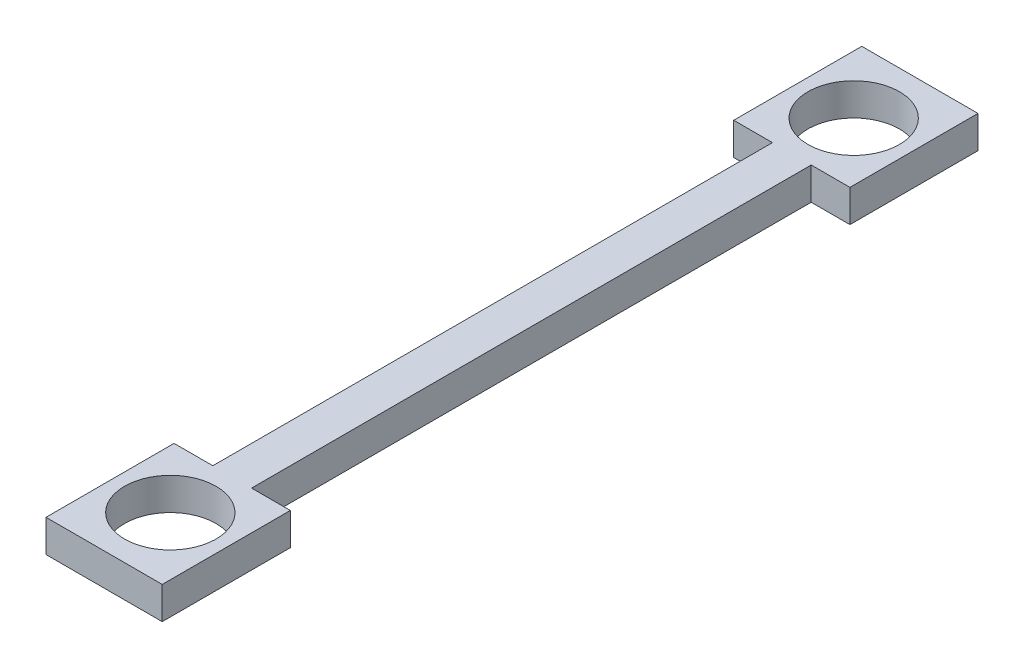
SolidWorks part; units mm, degrees
ref_plane "Front Plane" through (0, 0, 0) normal (0, 0, 1) x (1, 0, 0)
ref_plane "Top Plane" through (0, 0, 0) normal (0, 1, 0) x (1, 0, 0)
ref_plane "Right Plane" through (0, 0, 0) normal (1, 0, 0) x (0, 0, -1)
sketch "Sketch1" plane through (0, 0, 0) normal (0, 1, 0) x (1, 0, 0)
  line L0 (0, 11.5) -> (3.5, 11.5)
  line L5 (0, 0) -> (10, 0)
  line L6 (0, 0) -> (0, 11.5)
  line L8 (10, 0) -> (10, 11.5)
  line L10 (3.5, 11.5) -> (3.5, 63.5)
  line L12 (6.5, 11.5) -> (6.5, 63.5)
  line L13 (0, 75) -> (10, 75)
  line L14 (0, 75) -> (0, 63.5)
  line L16 (10, 75) -> (10, 63.5)
  line L17 (6.5, 11.5) -> (10, 11.5)
  line L18 (0, 63.5) -> (3.5, 63.5)
  line L19 (6.5, 63.5) -> (10, 63.5)
  line L20 (5, 76.9159) -> (5, -19.3491) construction
  dimension "D1" = 11.5
  dimension "D2" = 11.5
  dimension "D3" = 11.5
  dimension "D4" = 11.5
  dimension "D5" = 10
  dimension "D6" = 3
  dimension "D7" = 10
  dimension "D8" = 5
  dimension "D9" = 1.5
  dimension "D10" = 5
  dimension "D11" = 52
extrude "Boss-Extrude1" add sketch "Sketch1" along normal blind 3
sketch "Sketch2" plane through (0, 3, 0) normal (0, 1, 0) x (1, 0, 0)
  line L0 (5, 88.1197) -> (5, -25.223) construction
  line L1 (0, 11.5) -> (0, 0) construction
  line L2 (-27.6318, 37.5) -> (47.836, 37.5) construction
  line L3 (0, 0) -> (10, 0) construction
  line L4 (0, 63.5) -> (3.5, 63.5) construction
  circle A0 centre (5, 69.25) radius 4.25
  circle A1 centre (5, 5.75) radius 4.25
  dimension "D3" = 8.5
  dimension "D1" = 5
  dimension "D2" = 37.5
  dimension "D4" = 5.75
extrude "Cut-Extrude1" cut sketch "Sketch2" against normal blind 3
sketch "Sketch3" plane through (0, 0, 0) normal (0, 0, 1) x (1, 0, 0)
  line L4 (0, 0) -> (10, 0)
  line L5 (10, 0) -> (10, 3)
  line L6 (10, 3) -> (0, 3)
  line L7 (0, 3) -> (0, 0)
  line L8 (0, 0) -> (10, 0)
  line L9 (10, 0) -> (10, 3)
  line L10 (10, 3) -> (0, 3)
  line L11 (0, 3) -> (0, 0)
  dimension "D1" = 0
extrude "Boss-Extrude2" add sketch "Sketch3" along normal blind 0.4
sketch "Sketch4" plane through (0, 0, -75) normal (0, 0, -1) x (-1, 0, 0)
  line L4 (-10, 0) -> (0, 0)
  line L5 (0, 0) -> (0, 3)
  line L6 (0, 3) -> (-10, 3)
  line L7 (-10, 3) -> (-10, 0)
  line L8 (-10, 0) -> (0, 0)
  line L9 (0, 0) -> (0, 3)
  line L10 (0, 3) -> (-10, 3)
  line L11 (-10, 3) -> (-10, 0)
  dimension "D1" = 0
extrude "Boss-Extrude3" add sketch "Sketch4" along normal blind 0.4
sketch "Sketch5" plane through (10, 0, 0) normal (1, 0, 0) x (0, 0, -1)
  line L0 (63.5, 0) -> (75.4, 0) construction
  line L1 (75.4, 0) -> (75.4, 3) construction
  line L2 (75.4, 3) -> (63.5, 3) construction
  line L3 (63.5, 3) -> (63.5, 0) construction
  line L4 (-0.4, 0) -> (11.5, 0) construction
  line L5 (11.5, 0) -> (11.5, 3) construction
  line L6 (11.5, 3) -> (-0.4, 3) construction
  line L7 (-0.4, 3) -> (-0.4, 0) construction
  line L8 (63.5, 0) -> (75.4, 0)
  line L9 (75.4, 0) -> (75.4, 3)
  line L10 (75.4, 3) -> (63.5, 3)
  line L11 (63.5, 3) -> (63.5, 0)
  line L12 (-0.4, 0) -> (11.5, 0)
  line L13 (11.5, 0) -> (11.5, 3)
  line L14 (11.5, 3) -> (-0.4, 3)
  line L15 (-0.4, 3) -> (-0.4, 0)
extrude "Boss-Extrude4" add sketch "Sketch5" along normal blind 0.4
sketch "Sketch6" plane through (6.5, 0, 0) normal (1, 0, 0) x (0, 0, -1)
  line L4 (11.5, 0) -> (63.5, 0)
  line L5 (63.5, 0) -> (63.5, 3)
  line L6 (63.5, 3) -> (11.5, 3)
  line L7 (11.5, 3) -> (11.5, 0)
  line L8 (11.5, 0) -> (63.5, 0)
  line L9 (63.5, 0) -> (63.5, 3)
  line L10 (63.5, 3) -> (11.5, 3)
  line L11 (11.5, 3) -> (11.5, 0)
  dimension "D1" = 0
extrude "Boss-Extrude5" add sketch "Sketch6" along normal blind 0.4
sketch "Sketch7" plane through (0, 0, 0) normal (-1, 0, 0) x (0, 0, 1)
  line L0 (-11.5, 0) -> (0.4, 0) construction
  line L1 (0.4, 0) -> (0.4, 3) construction
  line L2 (0.4, 3) -> (-11.5, 3) construction
  line L3 (-11.5, 3) -> (-11.5, 0) construction
  line L4 (-75.4, 0) -> (-63.5, 0) construction
  line L5 (-63.5, 0) -> (-63.5, 3) construction
  line L6 (-63.5, 3) -> (-75.4, 3) construction
  line L7 (-75.4, 3) -> (-75.4, 0) construction
  line L8 (-11.5, 0) -> (0.4, 0)
  line L9 (0.4, 0) -> (0.4, 3)
  line L10 (0.4, 3) -> (-11.5, 3)
  line L11 (-11.5, 3) -> (-11.5, 0)
  line L12 (-75.4, 0) -> (-63.5, 0)
  line L13 (-63.5, 0) -> (-63.5, 3)
  line L14 (-63.5, 3) -> (-75.4, 3)
  line L15 (-75.4, 3) -> (-75.4, 0)
extrude "Boss-Extrude6" add sketch "Sketch7" along normal blind 0.4
sketch "Sketch8" plane through (3.5, 0, 0) normal (-1, 0, 0) x (0, 0, 1)
  line L4 (-63.5, 0) -> (-11.5, 0)
  line L5 (-11.5, 0) -> (-11.5, 3)
  line L6 (-11.5, 3) -> (-63.5, 3)
  line L7 (-63.5, 3) -> (-63.5, 0)
  line L8 (-63.5, 0) -> (-11.5, 0)
  line L9 (-11.5, 0) -> (-11.5, 3)
  line L10 (-11.5, 3) -> (-63.5, 3)
  line L11 (-63.5, 3) -> (-63.5, 0)
  dimension "D1" = 0
extrude "Boss-Extrude7" add sketch "Sketch8" along normal blind 0.4
sketch "Sketch9" plane through (3.1, 0, 0) normal (-1, 0, 0) x (0, 0, 1)
  line L4 (-63.5, 3) -> (-63.5, 0)
  line L5 (-63.5, 0) -> (-11.5, 0)
  line L6 (-11.5, 0) -> (-11.5, 3)
  line L7 (-11.5, 3) -> (-63.5, 3)
  line L8 (-63.5, 3) -> (-63.5, 0)
  line L9 (-63.5, 0) -> (-11.5, 0)
  line L10 (-11.5, 0) -> (-11.5, 3)
  line L11 (-11.5, 3) -> (-63.5, 3)
  dimension "D1" = 0
extrude "Cut-Extrude2" cut sketch "Sketch9" against normal blind 0.1
sketch "Sketch10" plane through (6.9, 0, 0) normal (1, 0, 0) x (0, 0, -1)
  line L4 (11.5, 3) -> (11.5, 0)
  line L5 (11.5, 0) -> (63.5, 0)
  line L6 (63.5, 0) -> (63.5, 3)
  line L7 (63.5, 3) -> (11.5, 3)
  line L8 (11.5, 3) -> (11.5, 0)
  line L9 (11.5, 0) -> (63.5, 0)
  line L10 (63.5, 0) -> (63.5, 3)
  line L11 (63.5, 3) -> (11.5, 3)
  dimension "D1" = 0
extrude "Cut-Extrude3" cut sketch "Sketch10" against normal blind 0.1
